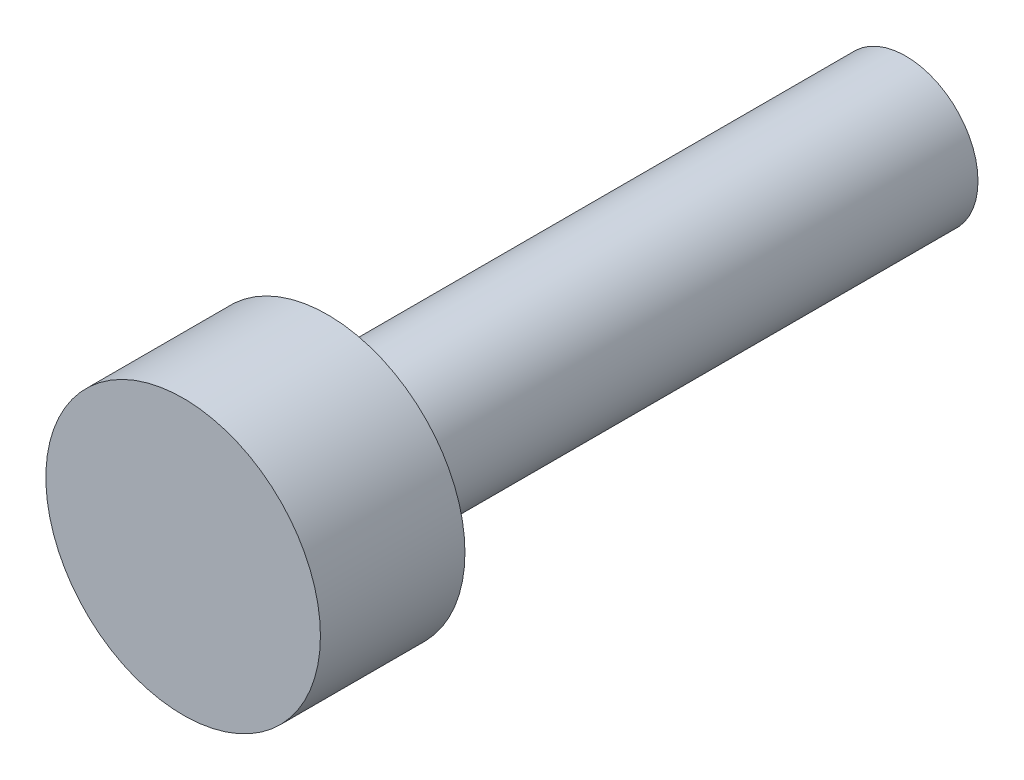
SolidWorks part; units mm, degrees
ref_plane "Front Plane" through (0, 0, 0) normal (0, 0, 1) x (1, 0, 0)
ref_plane "Top Plane" through (0, 0, 0) normal (0, 1, 0) x (1, 0, 0)
ref_plane "Right Plane" through (0, 0, 0) normal (1, 0, 0) x (0, 0, -1)
sketch "Sketch1" plane through (0, 0, 0) normal (0, 0, 1) x (1, 0, 0)
  circle A0 centre (0, 0) radius 1.5
  dimension "D1" = 3
extrude "Boss-Extrude1" add sketch "Sketch1" along normal blind 12
sketch "Sketch2" plane through (0, 0, 12) normal (0, 0, 1) x (1, 0, 0)
  circle A0 centre (0, 0) radius 2.85
  dimension "D1" = 5.7
extrude "Boss-Extrude2" add sketch "Sketch2" along normal blind 3
